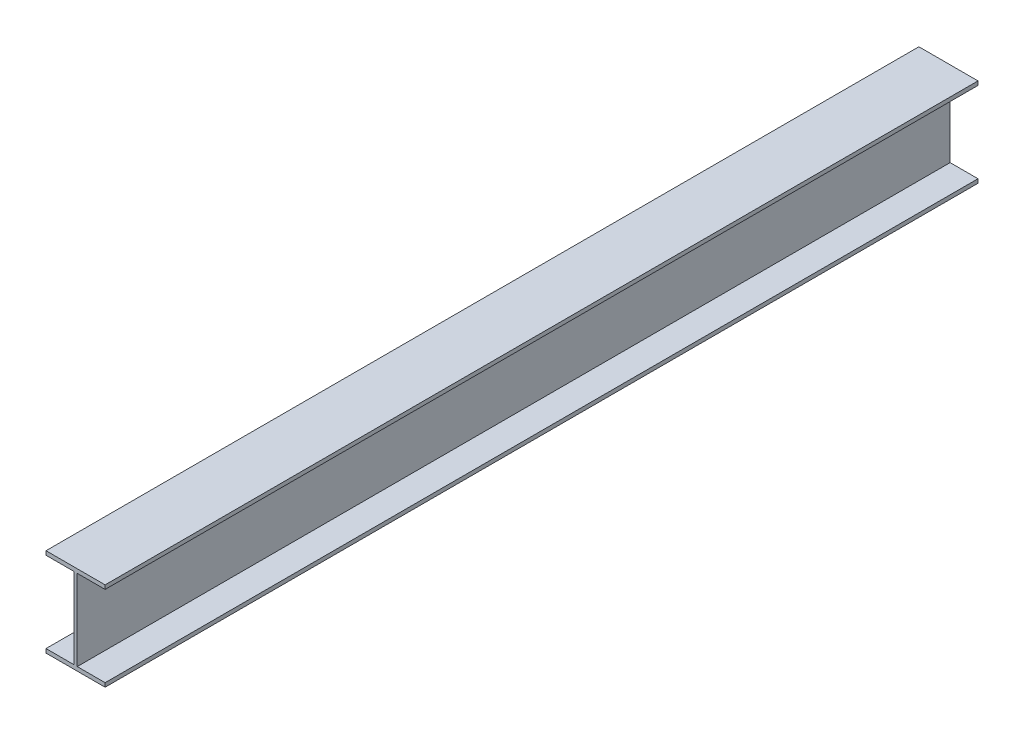
SolidWorks part; units mm, degrees
ref_plane "Alzado" through (0, 0, 0) normal (0, 0, 1) x (1, 0, 0)
ref_plane "Planta" through (0, 0, 0) normal (0, 1, 0) x (1, 0, 0)
ref_plane "Vista lateral" through (0, 0, 0) normal (1, 0, 0) x (0, 0, -1)
sketch "Croquis1" plane through (0, 0, 0) normal (0, 0, 1) x (1, 0, 0)
  line L0 (0, 0) -> (101.6, 0)
  line L1 (0, 0) -> (0, -6.8)
  line L2 (0, -6.8) -> (47.9, -6.8)
  line L3 (50.8, 0) -> (50.8, -152.4) construction
  line L4 (47.9, -6.8) -> (47.9, -145.6)
  line L5 (47.9, -145.6) -> (0, -145.6)
  line L6 (0, -145.6) -> (0, -152.4)
  line L7 (0, -152.4) -> (101.6, -152.4)
  line L8 (101.6, -145.6) -> (101.6, -152.4)
  line L9 (53.7, -145.6) -> (101.6, -145.6)
  line L10 (53.7, -6.8) -> (53.7, -145.6)
  line L11 (101.6, -6.8) -> (53.7, -6.8)
  line L12 (101.6, 0) -> (101.6, -6.8)
  dimension "D1" = 50.8
  dimension "D2" = 6.8
  dimension "D3" = 152.4
  dimension "D4" = 2.9
  dimension "D5" = 6.8
extrude "Saliente-Extruir1" add sketch "Croquis1" along normal blind 1500
